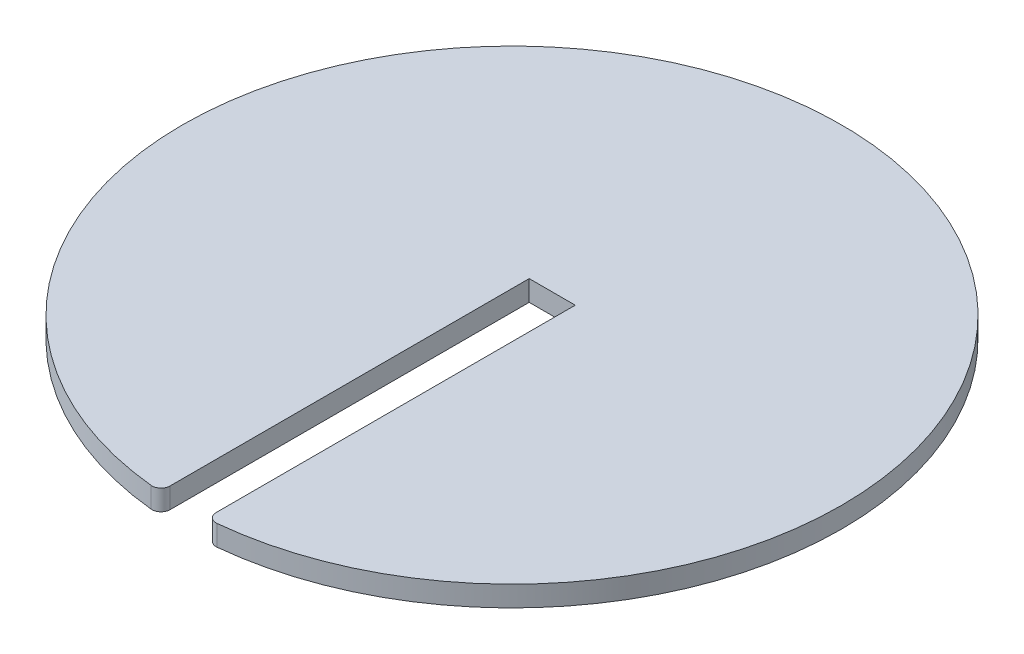
SolidWorks part; units mm, degrees
material "Custom Plastic"
ref_plane "Front Plane" through (0, 0, 0) normal (0, 0, 1) x (1, 0, 0)
ref_plane "Top Plane" through (0, 0, 0) normal (0, 1, 0) x (1, 0, 0)
ref_plane "Right Plane" through (0, 0, 0) normal (1, 0, 0) x (0, 0, -1)
sketch "Sketch1" plane through (0, 0, 0) normal (0, 1, 0) x (1, 0, 0)
  line L0 (2.4085, 1.9486) -> (2.4085, -20.2893)
  line L1 (5.9585, 8.1486) -> (2.4085, 8.1486)
  line L2 (5.9585, 8.1486) -> (5.9585, 1.9486)
  line L3 (5.9585, 1.9486) -> (5.9585, -20.2893)
  line L4 (2.4085, 8.1486) -> (2.4085, 1.9486)
  line L5 (5.9585, 8.1486) -> (2.4085, 1.9486) construction
  line L6 (5.9585, 1.9486) -> (2.4085, 8.1486) construction
  line L7 (-17.1481, 5.0486) -> (4.1835, 5.0486) construction
  arc A0 (5.9585, -20.2893) -> (2.4085, -20.2893) centre (4.1835, 5.0486) ccw
  point P0 (0, 0)
  dimension "D1" = 50.8
  dimension "D2" = 6.2
  dimension "D3" = 3.55
extrude "Boss-Extrude1" add sketch "Sketch1" along normal blind 1.5875
fillet "Fillet1" radius 0.7 2 edges at (2.4085, 0.7937, 20.2893) (5.9585, 0.7937, 20.2893)
